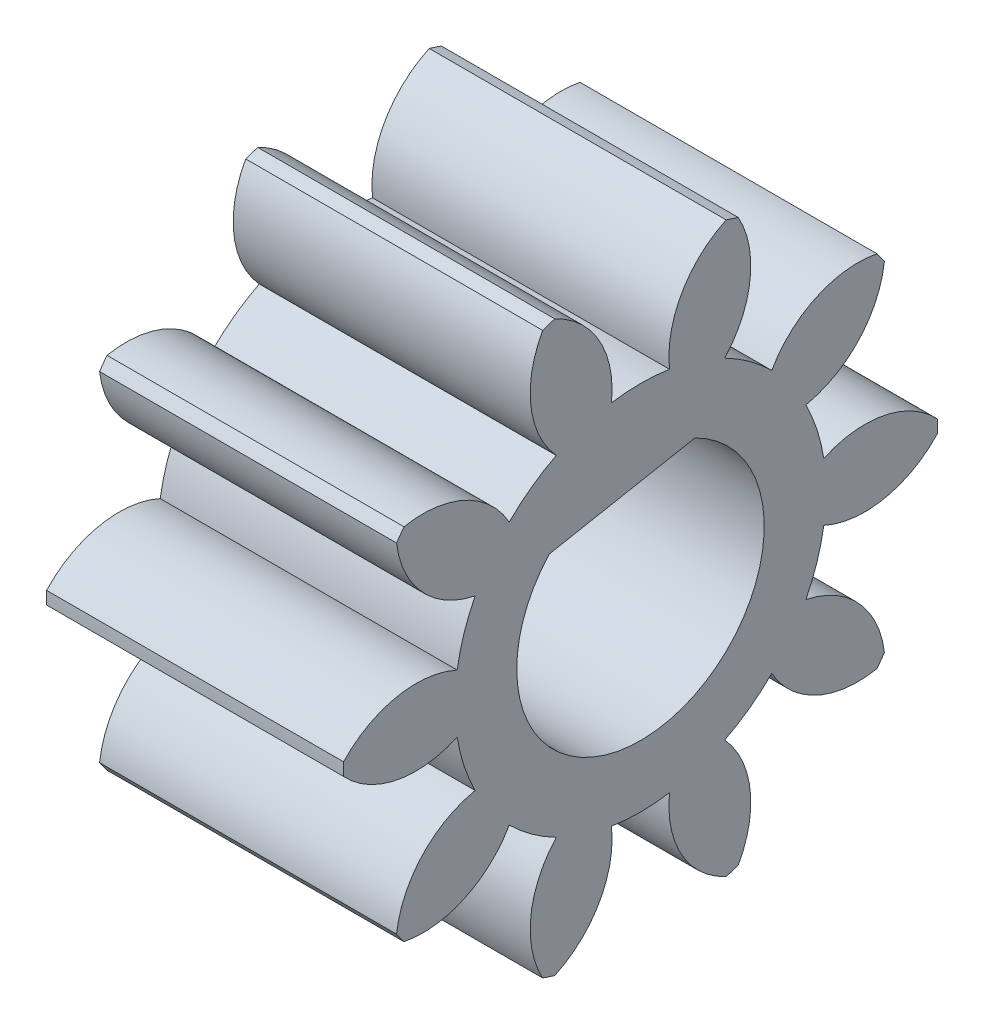
SolidWorks part; units mm, degrees
ref_plane "Plane1" through (0, 0, 0) normal (0, 0, 1) x (1, 0, 0)
ref_plane "Plane2" through (0, 0, 0) normal (0, 1, 0) x (1, 0, 0)
ref_plane "Plane3" through (0, 0, 0) normal (1, 0, 0) x (0, 0, -1)
sketch "HoldingSke" plane through (0, 0, 0) normal (0, 1, 0) x (1, 0, 0)
  line L0 (0, 0) -> (0.4924, -0.0868)
  line L1 (-15, 0) -> (100, 0) construction
  line L2 (0, 0) -> (-2.1039, 2.3779)
  line L3 (0, 0) -> (-11.863, 4.5341)
  line L4 (0, 0) -> (8.5048, 1.4996)
  line L5 (0, 0) -> (-46.8476, -17.4728)
  line L6 (0, 0) -> (-9.9476, -6.7116)
  line L7 (-2.1039, 2.3779) -> (8.6586, 51.2059)
  line L8 (-76.2, 54.61) -> (-76.1, 54.61)
  line L9 (-71.009, 38.7566) -> (-53.1078, 45.2721)
  line L10 (-76.2, 71.12) -> (104.1128, 71.12)
  line L11 (0, 0) -> (-12, 0)
  line L12 (-76.2, 101.6) -> (-76.133, 101.6)
  line L13 (24.9733, 27.94) -> (52.9518, 28.4284)
  line L14 (24.9733, 27.94) -> (24.9743, 27.94)
  line L15 (24.9733, 27.94) -> (100.4006, 29.5858)
  line L16 (-63.627, -2) -> (-12.827, -2)
  circle A0 centre (0, 0) radius 0.4
  circle A1 centre (0, 0) radius 7.499
  circle A2 centre (0, 0) radius 37.5
  circle A3 centre (0, 0) radius 0.4
  dimension "MHD" = 14.998
  dimension "Hub_dia" = 75
  dimension "Bore" = 0.8
  dimension "MBD" = 0.8
  dimension "Num_teeth" = 10
  dimension "Pitch" = 0.5
  dimension "Overall_len" = 50
  dimension "Show_teeth" = 10
  dimension "Thickness" = 12
  dimension "OAL" = 50.0001
  dimension "T_dim" = 0.1
  dimension "Ap" = 20
  dimension "H" = 19.05
  dimension "Pitch_radius" = 180.3128
  dimension "Width" = 12
  dimension "Backlash" = 0.067
  dimension "Addendum_fac" = 1
  dimension "Dedendum_fac" = 1.25
  dimension "Clearance_fac" = 0.25
  dimension "Dedendum_add" = 0.001
  dimension "Module" = 2
sketch "BasProSke" plane through (0, 0, 0) normal (0, 1, 0) x (1, 0, 0)
  line L0 (-10, 0) -> (60, 0) construction
  line L1 (0, 0) -> (0, 12)
  line L2 (0, 0) -> (12, 0)
  line L3 (12, 0) -> (12, 12)
  line L4 (12, 12) -> (0, 12)
  dimension "Thickness" = 12
  dimension "Diameter" = 24
revolve "Base-Revolve" add sketch "BasProSke" angle 360 about L0
sketch "TooCutSke" plane through (0, 0, 0) normal (1, 0, 0) x (0, 0, -1)
  line L1 (0, 0) -> (0, 107) construction
  line L2 (0, 0) -> (-1.6814, 9.8576) construction
  line L3 (0, 0) -> (-6.1153, 18.8209) construction
  line L4 (-1.6814, 9.8576) -> (-3.0576, 9.4105) construction
  arc A0 (1.1737, 7.4066) -> (-1.1737, 7.4066) centre (0, 0) ccw
  arc A1 (3.4979, 11.5054) -> (-3.4979, 11.5054) centre (0, 0) ccw
  circle A2 centre (0, 0) radius 10 construction
  circle A3 centre (0, 0) radius 9.3969 construction
  arc A4 (-1.1737, 7.4066) -> (-3.4979, 11.5054) centre (-5.1477, 7.8615) ccw
  arc A5 (3.4979, 11.5054) -> (1.1737, 7.4066) centre (5.1477, 7.8615) ccw
  dimension "Root_dia" = 14.998
  dimension "Overcut_dia" = 24.0508
  dimension "Pitch_dia" = 20
  dimension "Base_dia" = 18.7939
  dimension "Flank_rad" = 4
  dimension "Half_ang" = 18
  dimension "Half_CT" = 1.4471
extrude "ToothCut" cut sketch "TooCutSke" along normal through all
fillet "Breaks" [suppressed] radius 0.04
fillet "RootFillets" [suppressed] radius 0.501
pattern_circular "TeethCuts" count 10 every 36 about axis through (-10, 0, 0) along (1, 0, 0) of "ToothCut", "RootFillets", "Breaks"
sketch "HubNeaOneSke" plane through (0, 0, 0) normal (-1, 0, 0) x (0, 0, 1)
  circle A0 centre (0, 0) radius 7.499
  dimension "Diameter" = 14.998
extrude "HubNearOne" [suppressed] add sketch "HubNeaOneSke" along normal blind 38.0001
sketch "HubNeaBotSke" plane through (0, 0, 0) normal (-1, 0, 0) x (0, 0, 1)
  circle A0 centre (0, 0) radius 7.499
  dimension "Diameter" = 14.998
extrude "HubNearBoth" [suppressed] add sketch "HubNeaBotSke" along normal blind 19
ref_plane "FarPln" through (12, 0, 0) normal (1, 0, 0) x (0, 0, -1)
sketch "HubFarSke" plane through (12, 0, 0) normal (1, 0, 0) x (0, 0, -1)
  circle A0 centre (0, 0) radius 7.499
  dimension "Diameter" = 14.998
extrude "HubFar" [suppressed] add sketch "HubFarSke" along normal blind 19
sketch "BorSke" plane through (0, 0, 0) normal (1, 0, 0) x (0, 0, -1)
  circle A0 centre (0, 0) radius 0.4
  dimension "Diameter" = 0.8
extrude "Bore" cut sketch "BorSke" along normal mid plane 100.0001
sketch "KeySke" plane through (0, 0, 0) normal (1, 0, 0) x (0, 0, -1)
  line L0 (-0.05, 0) -> (-0.05, 0.5)
  line L1 (-0.05, 0.5) -> (0.05, 0.5)
  line L2 (0.05, 0.5) -> (0.05, 0)
  line L3 (0, 0) -> (0, 34) construction
  line L4 (-0.05, 0) -> (0.05, 0)
  dimension "Offset" = 0.5
  dimension "Width" = 0.1
extrude "Keyway" [suppressed] cut sketch "KeySke" along normal mid plane 100.0001
pattern_circular "Keyway2" [suppressed] count 2 every 90 about axis through (-10, 0, 0) along (1, 0, 0)
scale "Scale1" scale about centroid uniform scaling yes scale factor 0.5
sketch "Sketch2" plane through (9, 0, 0) normal (1, 0, 0) x (0, 0, -1)
  line L0 (-1.8477, 1.684) -> (1.0993, 2.2453)
  arc A0 (-1.8477, 1.684) -> (1.0993, 2.2453) centre (0, 0) ccw
  dimension "D1" = 5
  dimension "D2" = 3
extrude "Cut-Extrude1" cut sketch "Sketch2" against normal through all
equation "' \"Module@HoldingSke\" = 6.35"
equation "' \"Num_teeth@HoldingSke\" = 12"
equation "' \"Ap@HoldingSke\" =  20"
equation "' \"Ap@HoldingSke\" = 20"
equation "' \"Width@HoldingSke\" = 0.5 * 25.4"
equation "' \"Hub_dia@HoldingSke\"= 1 * 25.4"
equation "' \"Hub_dia@HoldingSke\" = 1 * 25.4"
equation "' \"Overall_len@HoldingSke\" = 1.0 * 25.4"
equation "' \"Bore@HoldingSke\" = 0.75 * 25.4"
equation "' \"T_dim@HoldingSke\" = 0.1 * 25.4"
equation "' \"Width@KeySke\" = 0.25 * 25.4"
equation "' \"Show_teeth@HoldingSke\" = 13"
equation "' \"Backlash@HoldingSke\" = 0.009 * 25.4"
equation "' \"Addendum_fac@HoldingSke\" = 1.0"
equation "' \"Dedendum_fac@HoldingSke\" = 1.25"
equation "' \"Dedendum_add@HoldingSke\" = 0.00005 * 25.4"
equation "' \"Clearance_fac@HoldingSke\" = 0.25"
equation "\"Pitch@HoldingSke\" = 1 / \"Module@HoldingSke\""
equation "\"Overcut_dia@TooCutSke\" = (\"Num_teeth@HoldingSke\" + 2 * \"Addendum_fac@HoldingSke\") / \"Pitch@HoldingSke\" + 0.002 * 25.4"
equation "\"Pitch_dia@TooCutSke\" = \"Num_teeth@HoldingSke\" / \"Pitch@HoldingSke\""
equation "\"Base_dia@TooCutSke\" = \"Num_teeth@HoldingSke\" / \"Pitch@HoldingSke\" * cos((\"Ap@HoldingSke\"  * 3.14159265 / 180))"
equation "\"Root_dia@TooCutSke\" = (\"Num_teeth@HoldingSke\" + 2) / \"Pitch@HoldingSke\" - 2 * (\"Addendum_fac@HoldingSke\" + \"Dedendum_fac@HoldingSke\") / \"Pitch@HoldingSke\" - \"Dedendum_add@HoldingSke\" * 2"
equation "\"Half_ang@TooCutSke\" = 180 / \"Num_teeth@HoldingSke\""
equation "\"Half_CT@TooCutSke\" = \"Num_teeth@HoldingSke\" / \"Pitch@HoldingSke\" * sin((3.14159265 / 2 / \"Num_teeth@HoldingSke\")) / 2 - 7 * \"Backlash@HoldingSke\" / 4"
equation "\"Flank_rad@TooCutSke\" = \"Num_teeth@HoldingSke\" / \"Pitch@HoldingSke\" / 5"
equation "\"Radius@RootFillets\" = \"Clearance_fac@HoldingSke\" / \"Pitch@HoldingSke\" + \"Dedendum_add@HoldingSke\""
equation "\"Break_rad@Breaks\" = 0.02 / \"Pitch@HoldingSke\""
equation "\"Thickness@HoldingSke\" = \"Width@HoldingSke\""
equation "\"OAL@HoldingSke\" = \"Thickness@HoldingSke\""
equation "\"MHD@HoldingSke\" = (\"Num_teeth@HoldingSke\" + 2) / \"Pitch@HoldingSke\" - 2 * (\"Addendum_fac@HoldingSke\" + \"Dedendum_fac@HoldingSke\")  / \"Pitch@HoldingSke\" - \"Dedendum_add@HoldingSke\" * 2"
equation "\"MBD@HoldingSke\" = (\"Num_teeth@HoldingSke\" + 2) / \"Pitch@HoldingSke\" - 2 * (\"Addendum_fac@HoldingSke\" + \"Dedendum_fac@HoldingSke\")  / \"Pitch@HoldingSke\" - \"Dedendum_add@HoldingSke\" * 2 - 0.002 * 25.4"
equation "\"MHD@HoldingSke\" = ((sgn( \"MHD@HoldingSke\" - \"Hub_dia@HoldingSke\" )-1)*( \"MHD@HoldingSke\" - \"Hub_dia@HoldingSke\" ))/-2+ \"Hub_dia@HoldingSke\""
equation "\"MBD@HoldingSke\" = ((sgn( \"MBD@HoldingSke\" - \"Bore@HoldingSke\" )-1)*( \"MBD@HoldingSke\" - \"Bore@HoldingSke\" ))/-2+ \"Bore@HoldingSke\""
equation "\"OAL@HoldingSke\" = ((sgn( \"OAL@HoldingSke\" - \"Overall_len@HoldingSke\" )+1)*( \"OAL@HoldingSke\" - \"Overall_len@HoldingSke\" ))/2 + \"Overall_len@HoldingSke\" + 0.000002 * 25.4"
equation "\"Num_teeth@TeethCuts\" = int( \"Show_teeth@HoldingSke\" ) + 1"
equation "\"Num_teeth@TeethCuts\" = ((sgn( \"Num_teeth@TeethCuts\" - \"Num_teeth@HoldingSke\" )-1)*( \"Num_teeth@TeethCuts\" - \"Num_teeth@HoldingSke\" ))/-2+ \"Num_teeth@HoldingSke\""
equation "\"Num_teeth@TeethCuts\" = ((sgn( \"Num_teeth@TeethCuts\" - 2.0)+1)*( \"Num_teeth@TeethCuts\" - 2.0))/2 +2.0"
equation "\"Angle@TeethCuts\" = 360.0 / \"Num_teeth@HoldingSke\""
equation "\"Diameter@BasProSke\" = (\"Num_teeth@HoldingSke\" + 2 * \"Addendum_fac@HoldingSke\") / \"Pitch@HoldingSke\""
equation "\"Thickness@BasProSke\"  = \"Thickness@HoldingSke\""
equation "' \"Fillet_rad@BasProSke\" =  \"Thickness@HoldingSke\" * 0.05"
equation "' \"Fillet_rad@BasProSke\" = \"Thickness@HoldingSke\" * 0.05"
equation "\"MHD@HoldingSke\" = ((sgn( \"MHD@HoldingSke\" - \"Root_dia@TooCutSke\" )-1)*( \"MHD@HoldingSke\" - \"Root_dia@TooCutSke\" ))/-2+ \"Root_dia@TooCutSke\""
equation "\"Diameter@HubNeaOneSke\" = \"MHD@HoldingSke\""
equation "\"Length@HubNearOne\" = \"OAL@HoldingSke\" - \"Thickness@BasProSke\""
equation "\"Diameter@HubNeaBotSke\" = \"MHD@HoldingSke\""
equation "\"Length@HubNearBoth\" = ( \"OAL@HoldingSke\" - \"Thickness@BasProSke\" ) / 2.0"
equation "\"Thickness@FarPln\" = \"Thickness@BasProSke\""
equation "\"Diameter@HubFarSke\" = \"MHD@HoldingSke\""
equation "\"Length@HubFar\" = ( \"OAL@HoldingSke\" - \"Thickness@BasProSke\" ) / 2.0"
equation "\"Diameter@BorSke\" = \"MBD@HoldingSke\""
equation "\"D1@Bore\" = \"OAL@HoldingSke\" * 2.0"
equation "\"D1@Keyway\" = \"OAL@HoldingSke\" * 2.0"
equation "\"Offset@KeySke\" = \"T_dim@HoldingSke\" + \"MBD@HoldingSke\" / 2.0"
